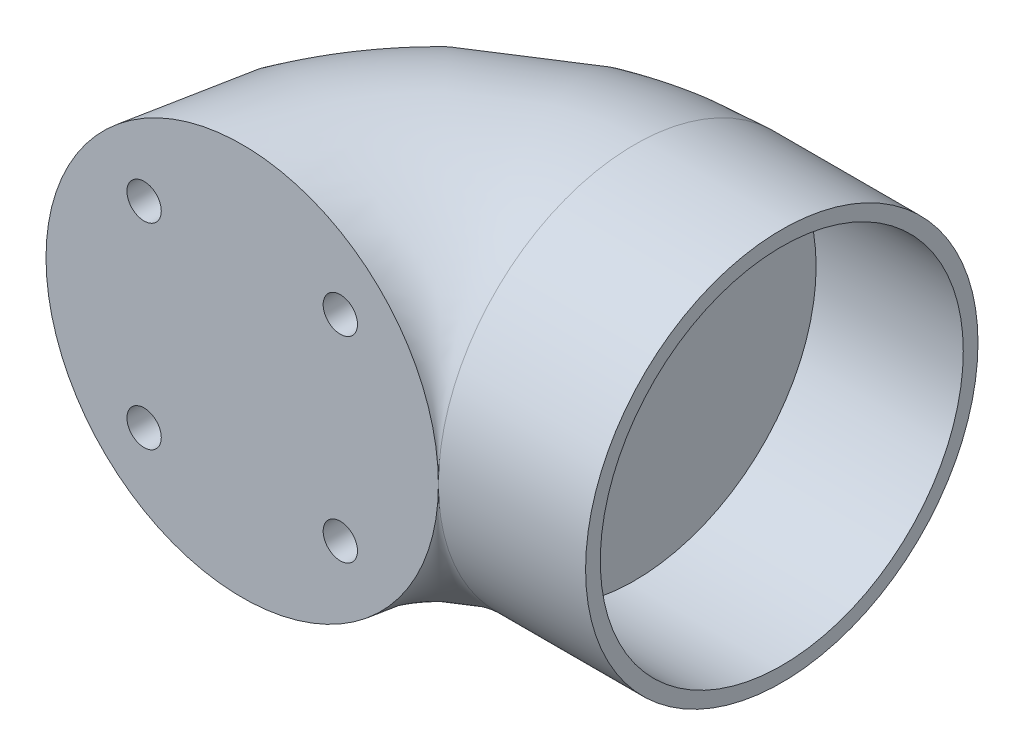
SolidWorks part; units mm, degrees
ref_plane "前视基准面" through (0, 0, 0) normal (0, 0, 1) x (1, 0, 0)
ref_plane "上视基准面" through (0, 0, 0) normal (0, 1, 0) x (1, 0, 0)
ref_plane "右视基准面" through (0, 0, 0) normal (1, 0, 0) x (0, 0, -1)
sketch "草图1" plane through (0, 0, 0) normal (0, 0, 1) x (1, 0, 0)
  circle A0 centre (0, 0) radius 20
sketch "草图2" plane through (0, 0, 0) normal (0, 1, 0) x (1, 0, 0)
  arc A1 (20, 20) -> (0, 0) centre (20, 0) ccw
sweep "扫描1" add profiles "草图1" path "草图2"
sketch "草图3" plane through (20, 0, 0) normal (1, 0, 0) x (0, 0, -1)
  circle A0 centre (20, 0) radius 20
  circle A1 centre (20, 0) radius 18.5
extrude "凸台-拉伸1" add sketch "草图3" along normal blind 15
sketch "草图4" plane through (0, 0, 0) normal (0, 0, 1) x (1, 0, 0)
  line L1 (-10, 10) -> (10, 10)
  line L2 (-10, 10) -> (-10, -10)
  line L3 (-10, -10) -> (10, -10)
  line L4 (10, 10) -> (10, -10)
  line L5 (-10, 10) -> (10, -10) construction
  line L6 (-10, -10) -> (10, 10) construction
  circle A0 centre (-10, 10) radius 1.75
  circle A1 centre (10, 10) radius 1.75
  circle A2 centre (10, -10) radius 1.75
  circle A3 centre (-10, -10) radius 1.75
  point P0 (0, 0)
  point P16 (0, 0)
  dimension "D1" = 4
extrude "切除-拉伸1" cut sketch "草图4" against normal through all contours L1 A0 L2 | L2 A0 L1 | L4 A1 L1 | L1 A1 L4 | L3 A2 L4 | L4 A2 L3 | L2 A3 L3 | L3 A3 L2
ref_plane "基准面1" through (0, 0, -40) normal (0, 0, 1) x (1, 0, 0)
sketch "草图5" plane through (0, 0, -40) normal (0, 0, 1) x (1, 0, 0)
  line L1 (-10, 10) -> (10, 10)
  line L2 (-10, 10) -> (-10, -10)
  line L3 (-10, -10) -> (10, -10)
  line L4 (10, 10) -> (10, -10)
  line L5 (-10, 10) -> (10, -10) construction
  line L6 (-10, -10) -> (10, 10) construction
  circle A0 centre (-10, 10) radius 4
  circle A1 centre (10, 10) radius 4
  circle A2 centre (10, -10) radius 4
  circle A3 centre (-10, -10) radius 4
  point P0 (0, 0)
  point P16 (0, 0)
  dimension "D1" = 4
  dimension "D2" = 8
extrude "切除-拉伸2" cut sketch "草图5" along normal blind 35 contours L4 A1 L1 | L1 A1 L4 | L2 A0 L1 | L1 A0 L2 | L3 A2 L4 | L4 A2 L3 | L2 A3 L3 | L3 A3 L2
